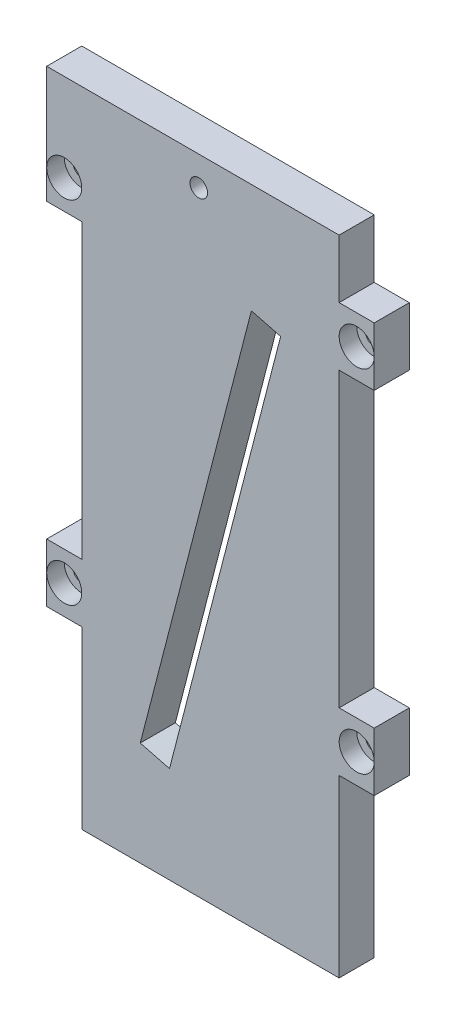
SolidWorks part; units mm, degrees
ref_plane "Plan de face" through (0, 0, 0) normal (0, 0, 1) x (1, 0, 0)
ref_plane "Plan de dessus" through (0, 0, 0) normal (0, 1, 0) x (1, 0, 0)
ref_plane "Plan de droite" through (0, 0, 0) normal (1, 0, 0) x (0, 0, -1)
sketch "Esquisse1" plane through (0, 0, 0) normal (0, 0, 1) x (1, 0, 0)
  line L0 (-6, 70) -> (-6, 90)
  line L1 (0, 0) -> (44, 0)
  line L2 (0, 0) -> (0, 10)
  line L3 (-6, 90) -> (44, 90)
  line L4 (44, 0) -> (44, 10)
  line L6 (44, 80) -> (44, 90)
  line L7 (0, 70) -> (-6, 70)
  line L9 (44, 80) -> (50, 80)
  line L10 (44, 20) -> (44, 70)
  line L11 (44, 70) -> (50, 70)
  line L12 (50, 80) -> (50, 70)
  line L13 (44, 10) -> (50, 10)
  line L14 (0, 20) -> (0, 70)
  line L15 (44, 20) -> (50, 20)
  line L16 (50, 10) -> (50, 20)
  line L17 (0, 10) -> (-6, 10)
  line L19 (0, 20) -> (-6, 20)
  line L20 (-6, 10) -> (-6, 20)
  dimension "D2" = 90
  dimension "D3" = 20
  dimension "D4" = 10
  dimension "D5" = 50
  dimension "D6" = 6
  dimension "D7" = 6
  dimension "D8" = 10
  dimension "D9" = 6
  dimension "D10" = 6
  dimension "D11" = 10
  dimension "D12" = 10
extrude "Boss.-Extru.1" add sketch "Esquisse1" along normal blind 6
sketch "Esquisse2" plane through (0, 0, 6) normal (0, 0, 1) x (1, 0, 0)
  line L1 (0, 10) -> (0, 0) construction
  line L2 (44, 90) -> (-6, 90) construction
  circle A0 centre (20, 85) radius 1.5
  dimension "D1" = 3
  dimension "D2" = 5
  dimension "D3" = 20
extrude "Enlèv. mat.-Extru.1" cut sketch "Esquisse2" against normal blind 6
sketch "Esquisse6" plane through (0, 0, 6) normal (0, 0, 1) x (1, 0, 0)
  line L1 (-6, 90) -> (-6, 70) construction
  line L3 (0, 20) -> (-6, 20) construction
  line L4 (-6, 20) -> (-6, 10) construction
  line L5 (44, 70) -> (50, 70) construction
  line L8 (-6, 70) -> (0, 70) construction
  line L10 (50, 70) -> (50, 80) construction
  line L11 (50, 20) -> (44, 20) construction
  line L12 (50, 10) -> (50, 20) construction
  circle A0 centre (-3, 75) radius 1.5
  circle A1 centre (-3, 15) radius 1.5
  circle A2 centre (47, 15) radius 1.5
  circle A3 centre (47, 75) radius 1.5
  point P4 (-6, 80)
  point P7 (-3, 70)
  point P14 (50, 75)
  dimension "D1" = 3
  dimension "D2" = 5
  dimension "D3" = 5
  dimension "D4" = 5
  dimension "D6" = 3
  dimension "D7" = 5
  dimension "D8" = 3
  dimension "D9" = 3
  dimension "D10" = 5
  dimension "D11" = 3
  dimension "D12" = 3
  dimension "D5" = 3
extrude "Enlèv. mat.-Extru.4" cut sketch "Esquisse6" against normal blind 6
sketch "Esquisse7" plane through (0, 0, 6) normal (0, 0, 1) x (1, 0, 0)
  circle A0 centre (-3, 15) radius 2.995
  circle A1 centre (-3, 75) radius 2.995
  circle A2 centre (47, 75) radius 2.995
  circle A3 centre (47, 15) radius 2.995
  dimension "D1" = 5.99
  dimension "D2" = 5.99
  dimension "D3" = 5.99
  dimension "D4" = 5.99
extrude "Enlèv. mat.-Extru.5" cut sketch "Esquisse7" against normal blind 3
sketch "Esquisse8" plane through (0, 0, 0) normal (0, 0, -1) x (-1, 0, 0)
  line L1 (0, 0) -> (-44, 0)
  line L2 (0, 0) -> (0, -20)
  line L3 (0, -20) -> (-44, -20)
  line L4 (-44, 0) -> (-44, -20)
  dimension "D1" = 44
  dimension "D2" = 20
extrude "Boss.-Extru.2" add sketch "Esquisse8" against normal blind 6
sketch "Esquisse9" plane through (0, 0, 0) normal (0, 0, -1) x (-1, 0, 0)
  line L0 (0, 10) -> (0, -20) construction
  line L1 (0, -13) -> (-25, -13)
  line L2 (0, -13) -> (0, -6.5)
  line L3 (0, -6.5) -> (-25, -6.5)
  line L4 (-25, -13) -> (-25, -6.5)
  line L5 (-44, -20) -> (0, -20) construction
  dimension "D1" = 25
  dimension "D2" = 7
  dimension "D3" = 6.5
extrude "Enlèv. mat.-Extru.6" cut sketch "Esquisse9" against normal blind 4
sketch "Esquisse10" plane through (0, 0, 0) normal (0, 0, -1) x (-1, 0, 0)
  line L0 (-34, 70) -> (-15, -3.5)
  line L1 (-15, -3.5) -> (-10, -2.2075)
  line L2 (-10, -2.2075) -> (-29, 71.2925)
  line L3 (-29, 71.2925) -> (-34, 70)
  line L4 (-44, 20) -> (-44, 70) construction
  line L5 (0, 10) -> (0, -6.5) construction
  line L6 (-44, 90) -> (6, 90) construction
  line L7 (0, -6.5) -> (-25, -6.5) construction
  dimension "D1" = 10
  dimension "D2" = 15
  dimension "D3" = 10
  dimension "D4" = 20
  dimension "D5" = 3
extrude "Enlèv. mat.-Extru.7" cut sketch "Esquisse10" against normal blind 6
